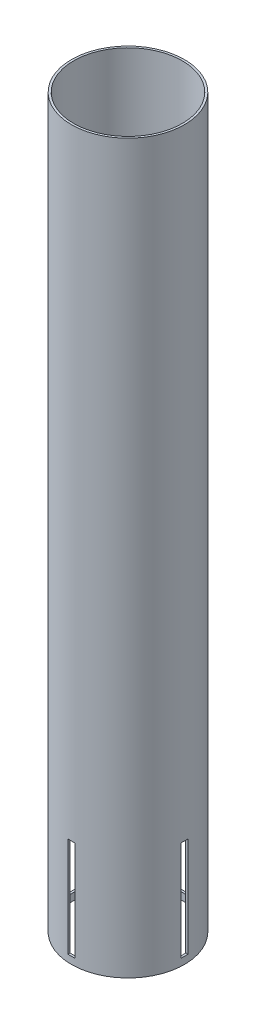
SolidWorks part; units mm, degrees
ref_plane "Front Plane" through (0, 0, 0) normal (0, 0, 1) x (1, 0, 0)
ref_plane "Top Plane" through (0, 0, 0) normal (0, 1, 0) x (1, 0, 0)
ref_plane "Right Plane" through (0, 0, 0) normal (1, 0, 0) x (0, 0, -1)
sketch "Sketch1" plane through (0, 0, 0) normal (0, 1, 0) x (1, 0, 0)
  circle A0 centre (0, 0) radius 39.6
  circle A1 centre (0, 0) radius 38.1
  dimension "D1" = 79.2
  dimension "D2" = 76.2
extrude "Boss-Extrude1" add sketch "Sketch1" along normal blind 510
sketch "Sketch2" plane through (0, 0, 0) normal (0, 0, 1) x (1, 0, 0)
  line L1 (-2.5, 5) -> (2.5, 5)
  line L2 (-2.5, 5) -> (-2.5, 75)
  line L3 (-2.5, 75) -> (2.5, 75)
  line L4 (2.5, 5) -> (2.5, 75)
  point P4 (0, 5)
  dimension "D1" = 5
  dimension "D2" = 70
  dimension "D3" = 5
extrude "Cut-Extrude1" cut sketch "Sketch2" against normal through all
pattern_circular "CirPattern1" count 4 over 360 about axis through (0, 0, 0) along (0, 1, 0) of "Cut-Extrude1"
